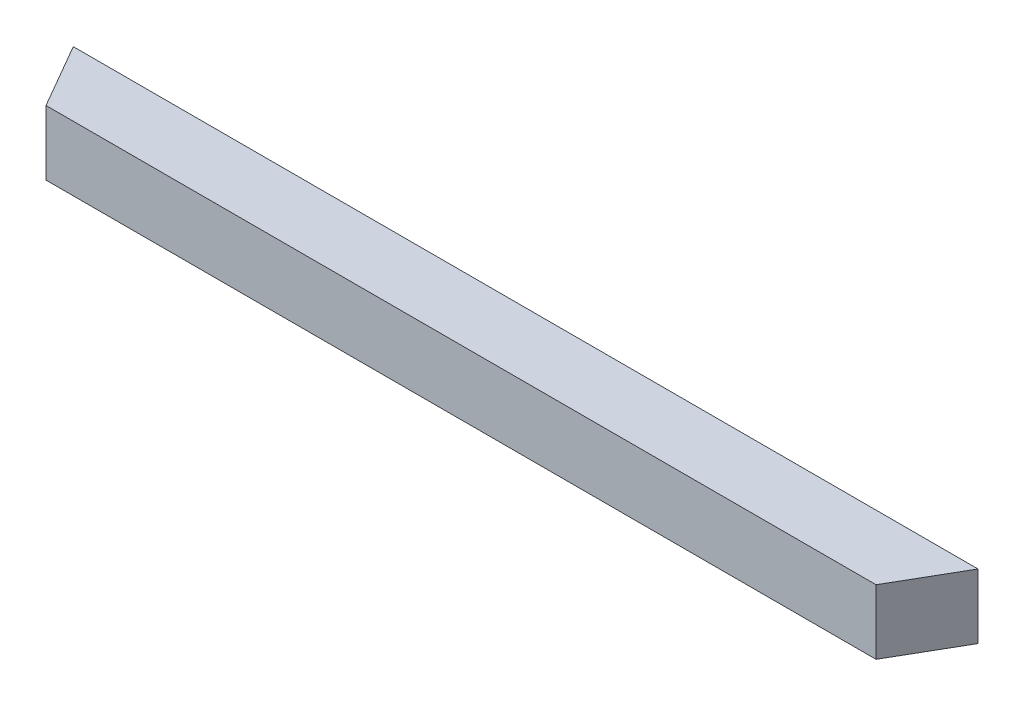
SolidWorks part; units mm, degrees
ref_plane "Front Plane" through (0, 0, 0) normal (0, 0, 1) x (1, 0, 0)
ref_plane "Top Plane" through (0, 0, 0) normal (0, 1, 0) x (1, 0, 0)
ref_plane "Right Plane" through (0, 0, 0) normal (1, 0, 0) x (0, 0, -1)
sketch "Sketch2" plane through (0, 0, 0) normal (0, 1, 0) x (1, 0, 0)
  line L0 (-140, 0) -> (140, 0)
  line L1 (-128.453, -20) -> (128.453, -20)
  line L2 (-128.453, -20) -> (-140, 0)
  line L3 (128.453, -20) -> (140, 0)
  point P4 (0, 0)
  point P7 (0, -20)
  dimension "D1" = 60
  dimension "D2" = 60
  dimension "D3" = 20
  dimension "D4" = 280
extrude "Boss-Extrude1" add sketch "Sketch2" along normal blind 20
